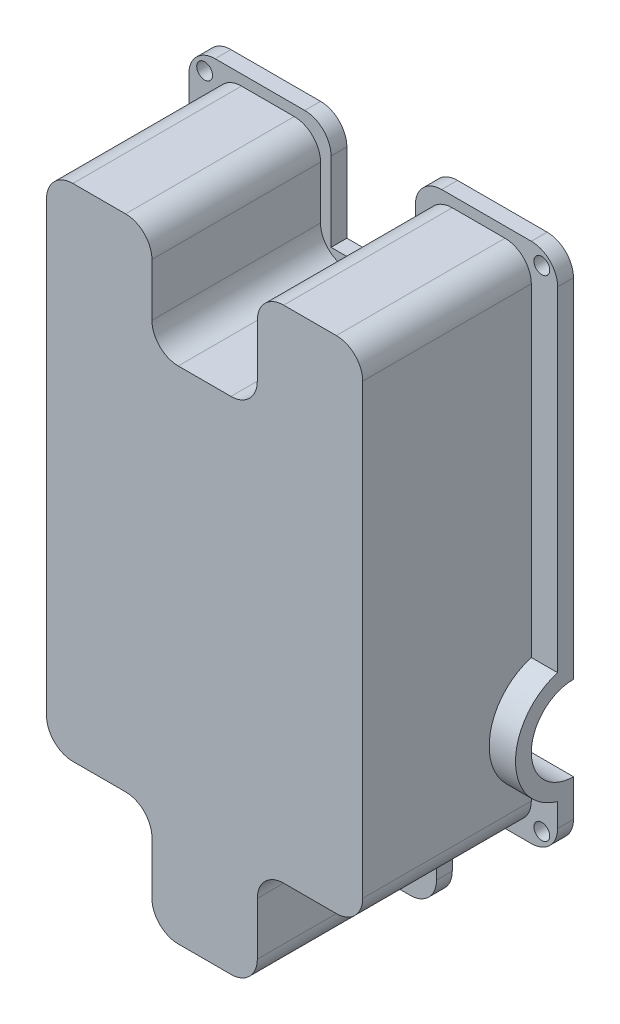
SolidWorks part; units mm, degrees
ref_plane "Front Plane" through (0, 0, 0) normal (0, 0, 1) x (1, 0, 0)
ref_plane "Top Plane" through (0, 0, 0) normal (0, 1, 0) x (1, 0, 0)
ref_plane "Right Plane" through (0, 0, 0) normal (1, 0, 0) x (0, 0, -1)
sketch "Sketch1" plane through (0, 0, 0) normal (0, 0, 1) x (1, 0, 0)
  line L1 (-35, 59.5) -> (35, 59.5)
  line L2 (-35, 59.5) -> (-35, -59.5)
  line L3 (-35, -59.5) -> (35, -59.5)
  line L4 (35, 59.5) -> (35, -59.5)
  line L5 (0, -59.5) -> (0, 59.5) construction
  line L6 (-35, 0) -> (35, 0) construction
  point P0 (0, 0)
  dimension "D1" = 119
  dimension "D2" = 70
extrude "Boss-Extrude1" add sketch "Sketch1" along normal blind 35
sketch "Sketch2" plane through (35, 0, 0) normal (1, 0, 0) x (0, 0, -1)
  line L0 (0, -59.5) -> (0, 59.5) construction
  circle A0 centre (0, -19.5) radius 8
  dimension "D1" = 16
  dimension "D2" = 40
extrude "Cut-Extrude1" cut sketch "Sketch2" against normal blind 8
sketch "Sketch3" plane through (-35, 0, 0) normal (-1, 0, 0) x (0, 0, 1)
  line L0 (0, 59.5) -> (0, -59.5) construction
  circle A0 centre (0, 19.5) radius 8
  dimension "D1" = 16
  dimension "D2" = 79
extrude "Cut-Extrude2" cut sketch "Sketch3" against normal blind 8
sketch "Sketch4" plane through (0, 0, 0) normal (0, 0, -1) x (-1, 0, 0)
  line L0 (-35, -11.5) -> (-35, 59.5) construction
  line L1 (-27, 54.026) -> (-13, 54.026)
  line L2 (-27, 54.026) -> (-27, -34.974)
  line L3 (-27, -34.974) -> (-13, -34.974)
  line L4 (-13, 54.026) -> (-13, -34.974)
  line L5 (-7, 34.5) -> (7, 34.5)
  line L6 (-7, 34.5) -> (-7, -54.5)
  line L7 (-7, -54.5) -> (7, -54.5)
  line L8 (7, 34.5) -> (7, -54.5)
  line L9 (13, 54.026) -> (27, 54.026)
  line L10 (13, 54.026) -> (13, -34.974)
  line L11 (13, -34.974) -> (27, -34.974)
  line L12 (27, 54.026) -> (27, -34.974)
  line L13 (35, 59.5) -> (35, 27.5) construction
  line L14 (35, -59.5) -> (-35, -59.5) construction
  line L15 (-35, 59.5) -> (35, 59.5) construction
  dimension "D1" = 8
  dimension "D2" = 8
  dimension "D3" = 14
  dimension "D4" = 14
  dimension "D5" = 14
  dimension "D6" = 6
  dimension "D7" = 6
  dimension "D8" = 89
  dimension "D9" = 89
  dimension "D10" = 5
  dimension "D11" = 25
extrude "Cut-Extrude3" cut sketch "Sketch4" against normal blind 32
sketch "Sketch5" plane through (7, 0, 0) normal (-1, 0, 0) x (0, 0, 1)
  line L0 (0, 27.5) -> (0, 11.5)
  arc A0 (0, 11.5) -> (0, 27.5) centre (0, 19.5) ccw construction
  arc A1 (0, 11.5) -> (0, 27.5) centre (0, 19.5) ccw
extrude "Cut-Extrude4" cut sketch "Sketch5" against normal up to next
sketch "Sketch6" plane through (-7, 0, 0) normal (1, 0, 0) x (0, 0, -1)
  line L0 (0, -11.5) -> (0, -27.5)
  line L4 (0, -54.5) -> (0, 34.5)
  line L5 (0, 34.5) -> (-32, 34.5)
  line L6 (-32, 34.5) -> (-32, -54.5)
  line L7 (-32, -54.5) -> (0, -54.5)
  line L8 (0, -54.5) -> (0, 34.5)
  line L9 (0, 34.5) -> (-32, 34.5)
  line L10 (-32, 34.5) -> (-32, -54.5)
  line L11 (-32, -54.5) -> (0, -54.5)
  arc A0 (0, -11.5) -> (0, -27.5) centre (0, -19.5) ccw construction
  arc A1 (0, -11.5) -> (0, -27.5) centre (0, -19.5) ccw
  line M5 (0, -54.5) -> (0, 34.5)
  dimension "D1" = 0
extrude "Cut-Extrude5" cut sketch "Sketch6" against normal up to next contours A1 M5
sketch "Sketch7" plane through (0, 0, 0) normal (0, 0, -1) x (-1, 0, 0)
  line L0 (0, 59.5) -> (0, -59.5) construction
  line L1 (-35, 59.5) -> (35, 59.5) construction
  line L2 (35, -59.5) -> (-35, -59.5) construction
  line L3 (12, -59.5) -> (12, -39.5)
  line L4 (-8, 59.5) -> (8, 59.5)
  line L5 (-8, 59.5) -> (-8, 39.5)
  line L6 (-8, 39.5) -> (8, 39.5)
  line L7 (8, 59.5) -> (8, 39.5)
  line L8 (-35, -59.5) -> (-12, -59.5)
  line L9 (-35, -59.5) -> (-35, -39.5)
  line L10 (-35, -39.5) -> (-12, -39.5)
  line L11 (-12, -59.5) -> (-12, -39.5)
  line L12 (35, -39.5) -> (12, -39.5)
  line L13 (35, -59.5) -> (35, -39.5)
  line L14 (35, -59.5) -> (12, -59.5)
  dimension "D1" = 16
  dimension "D2" = 20
  dimension "D3" = 20
  dimension "D4" = 23
extrude "Cut-Extrude6" cut sketch "Sketch7" against normal through all
sketch "Sketch8" plane through (35, 0, 0) normal (1, 0, 0) x (0, 0, -1)
  line L4 (-3, 59.5) -> (-35, 59.5)
  line L5 (-35, 59.5) -> (-35, -39.5)
  line L6 (-3, -39.5) -> (-3, -30.083)
  line L7 (-3, -8.917) -> (-3, 59.5)
  line L8 (-3, -39.5) -> (-3, -30.083)
  line L9 (-3, -8.917) -> (-3, 59.5)
  line L10 (-35, -39.5) -> (-3, -39.5)
  arc A3 (-3, -8.917) -> (-3, -30.083) centre (0, -19.5) ccw
  arc A4 (-3, -8.917) -> (-3, -30.083) centre (0, -19.5) ccw
  dimension "D1" = 3
extrude "Cut-Extrude7" cut sketch "Sketch8" against normal blind 5
sketch "Sketch9" plane through (0, -39.5, 0) normal (0, -1, 0) x (1, 0, 0)
  line L1 (30, 3) -> (12, 3)
  line L2 (30, 3) -> (30, 35)
  line L3 (30, 35) -> (12, 35)
  line L4 (12, 3) -> (12, 35)
extrude "Cut-Extrude8" cut sketch "Sketch9" against normal blind 2
sketch "Sketch10" plane through (0, -59.5, 0) normal (0, -1, 0) x (1, 0, 0)
  line L1 (12, 3) -> (-12, 3)
  line L2 (12, 3) -> (12, 35)
  line L3 (12, 35) -> (-12, 35)
  line L4 (-12, 3) -> (-12, 35)
extrude "Cut-Extrude9" cut sketch "Sketch10" against normal blind 2
sketch "Sketch11" plane through (0, -39.5, 0) normal (0, -1, 0) x (1, 0, 0)
  line L1 (-35, 35) -> (-12, 35)
  line L2 (-35, 35) -> (-35, 3)
  line L3 (-35, 3) -> (-12, 3)
  line L4 (-12, 35) -> (-12, 3)
extrude "Cut-Extrude10" cut sketch "Sketch11" against normal blind 2
sketch "Sketch12" plane through (-12, 0, 0) normal (-1, 0, 0) x (0, 0, 1)
  line L1 (35, -57.5) -> (3, -57.5)
  line L2 (35, -57.5) -> (35, -37.5)
  line L3 (35, -37.5) -> (3, -37.5)
  line L4 (3, -57.5) -> (3, -37.5)
extrude "Cut-Extrude11" cut sketch "Sketch12" against normal blind 2
sketch "Sketch13" plane through (12, 0, 0) normal (1, 0, 0) x (0, 0, -1)
  line L1 (-35, -57.5) -> (-3, -57.5)
  line L2 (-35, -57.5) -> (-35, -37.5)
  line L3 (-35, -37.5) -> (-3, -37.5)
  line L4 (-3, -57.5) -> (-3, -37.5)
extrude "Cut-Extrude12" cut sketch "Sketch13" against normal blind 2
sketch "Sketch14" plane through (0, 59.5, 0) normal (0, 1, 0) x (1, 0, 0)
  line L1 (30, -3) -> (-35, -3)
  line L2 (30, -3) -> (30, -35)
  line L3 (30, -35) -> (-35, -35)
  line L4 (-35, -3) -> (-35, -35)
extrude "Cut-Extrude13" cut sketch "Sketch14" against normal blind 2
sketch "Sketch15" plane through (0, 39.5, 0) normal (0, 1, 0) x (1, 0, 0)
  line L1 (8, -3) -> (-8, -3)
  line L2 (8, -3) -> (8, -35)
  line L3 (8, -35) -> (-8, -35)
  line L4 (-8, -3) -> (-8, -35)
extrude "Cut-Extrude15" cut sketch "Sketch15" against normal blind 2
sketch "Sketch17" plane through (-8, 0, 0) normal (1, 0, 0) x (0, 0, -1)
  line L1 (-3, 57.5) -> (-35, 57.5)
  line L2 (-3, 57.5) -> (-3, 37.5)
  line L3 (-3, 37.5) -> (-35, 37.5)
  line L4 (-35, 57.5) -> (-35, 37.5)
extrude "Cut-Extrude16" cut sketch "Sketch17" against normal blind 2
sketch "Sketch18" plane through (8, 0, 0) normal (-1, 0, 0) x (0, 0, 1)
  line L1 (3, 37.5) -> (35, 37.5)
  line L2 (3, 37.5) -> (3, 57.5)
  line L3 (3, 57.5) -> (35, 57.5)
  line L4 (35, 37.5) -> (35, 57.5)
extrude "Cut-Extrude17" cut sketch "Sketch18" against normal blind 2
sketch "Sketch20" plane through (-35, 0, 0) normal (-1, 0, 0) x (0, 0, 1)
  line L1 (3, 57.5) -> (35, 57.5)
  line L2 (3, 57.5) -> (3, -37.5)
  line L3 (3, -37.5) -> (35, -37.5)
  line L4 (35, 57.5) -> (35, -37.5)
extrude "Cut-Extrude18" cut sketch "Sketch20" against normal blind 5
sketch "Sketch21" plane through (0, 0, 0) normal (0, 0, -1) x (-1, 0, 0)
  line L0 (-35, -11.5) -> (-35, 59.5) construction
  line L1 (-32, 56.5) -> (32, 56.5) construction
  line L2 (-32, 56.5) -> (-32, -36.5) construction
  line L3 (-32, -36.5) -> (32, -36.5) construction
  line L4 (32, 56.5) -> (32, -36.5) construction
  line L5 (-35, 59.5) -> (-8, 59.5) construction
  line L6 (35, 59.5) -> (35, 27.5) construction
  line L7 (8, 59.5) -> (35, 59.5) construction
  line L8 (-12, -39.5) -> (-35, -39.5) construction
  circle A0 centre (-32, 56.5) radius 1.5
  circle A1 centre (32, 56.5) radius 1.5
  circle A2 centre (32, -36.5) radius 1.5
  circle A3 centre (-32, -36.5) radius 1.5
  dimension "D7" = 3
  dimension "D8" = 3
  dimension "D9" = 3
  dimension "D10" = 3
  dimension "D1" = 3
  dimension "D2" = 3
  dimension "D3" = 3
  dimension "D4" = 3
  dimension "D5" = 3
  dimension "D6" = 3
extrude "Cut-Extrude20" cut sketch "Sketch21" against normal blind 10
fillet "Fillet1" radius 5 12 edges at (-10, 57.5, 19) (-10, 37.5, 19) (10, 37.5, 19) (10, 57.5, 19) (30, 57.5, 19) (30, -37.5, 19) (10, -37.5, 19) (10, -57.5, 19) (-10, -37.5, 19) (-30, -37.5, 19) (-30, 57.5, 19) (-10, -57.5, 19)
fillet "Fillet2" radius 5 10 edges at (35, 59.5, 1.5) (8, 59.5, 1.5) (-8, 59.5, 1.5) (-35, 59.5, 1.5) (-35, 11.6473, 1.5281) (-35, 27.3527, 1.5281) (-35, -39.5, 1.5) (-12, -59.5, 1.5) (12, -59.5, 1.5) (35, -39.5, 1.5)
